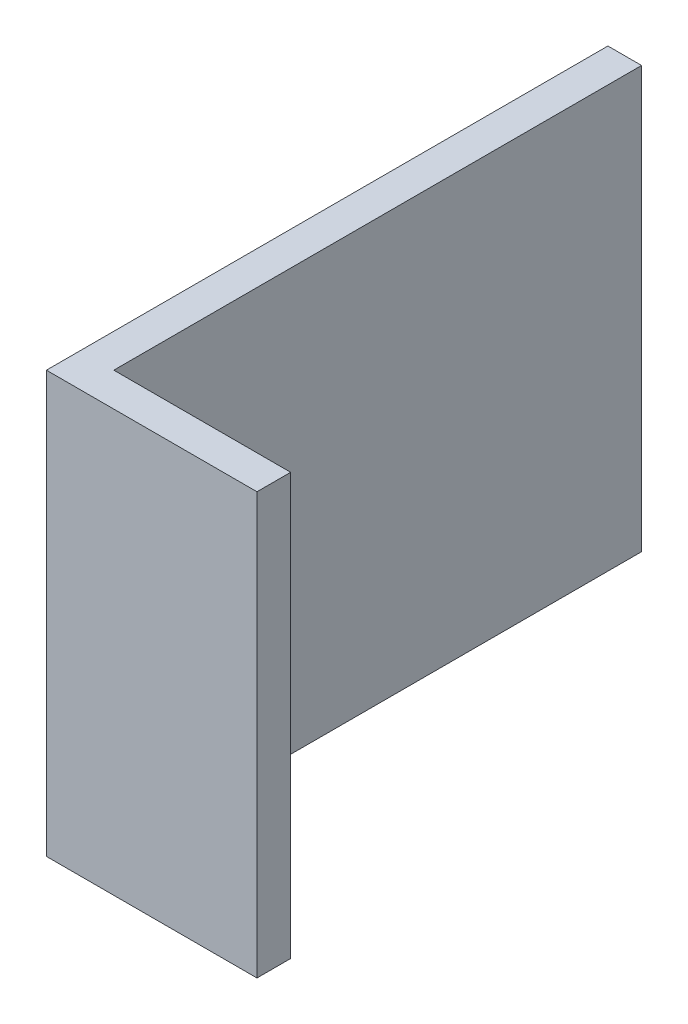
SolidWorks part; units mm, degrees
ref_plane "Front Plane" through (0, 0, 0) normal (0, 0, 1) x (1, 0, 0)
ref_plane "Top Plane" through (0, 0, 0) normal (0, 1, 0) x (1, 0, 0)
ref_plane "Right Plane" through (0, 0, 0) normal (1, 0, 0) x (0, 0, -1)
sketch "Sketch1" plane through (0, 0, 0) normal (0, 1, 0) x (1, 0, 0)
  line L0 (19.05, 0) -> (0, 0)
  line L1 (0, 0) -> (0, 50.8)
  dimension "D1" = 50.8
  dimension "D2" = 19.05
extrude "Extrude-Thin1" add sketch "Sketch1" along normal blind 38.1 thin
